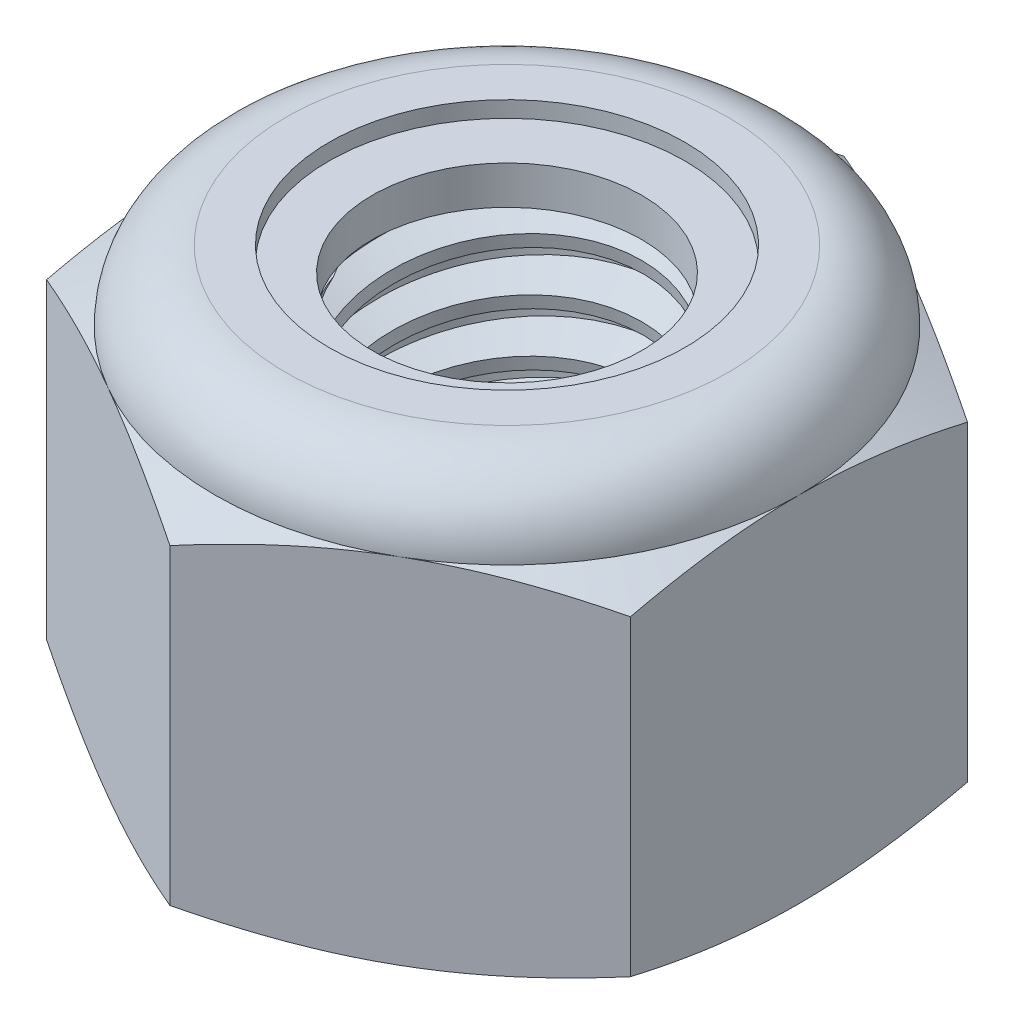
SolidWorks part; units mm, degrees
material "Stainless Steel (ferritic)"
ref_plane "Front" through (0, 0, 0) normal (0, 0, 1) x (1, 0, 0)
ref_plane "Top" through (0, 0, 0) normal (0, 1, 0) x (1, 0, 0)
ref_plane "Right" through (0, 0, 0) normal (1, 0, 0) x (0, 0, -1)
sketch "Sketch1" plane through (0, 0, 0) normal (0, 1, 0) x (1, 0, 0)
  line L1 (0, 3.1754) -> (-2.75, 1.5877)
  line L2 (-2.75, 1.5877) -> (-2.75, -1.5877)
  line L3 (-2.75, -1.5877) -> (0, -3.1754)
  line L4 (0, -3.1754) -> (2.75, -1.5877)
  line L5 (2.75, -1.5877) -> (2.75, 1.5877)
  line L6 (2.75, 1.5877) -> (0, 3.1754)
  circle A0 centre (0, 0) radius 2.75 construction
  dimension "Hex Flats" = 5.5
extrude "Extrude1" add sketch "Sketch1" along normal blind 4
sketch "Sketch2" plane through (0, 0, 0) normal (1, 0, 0) x (0, 0, -1)
  line L0 (-1.5, 0) -> (-1.5, 4) construction
  line L1 (0, 0) -> (1.5, 0)
  line L2 (0, 0) -> (0, 4)
  line L3 (0, 4) -> (1.5, 4)
  line L4 (1.5, 0) -> (1.5, 4)
  line L5 (-1.5877, 4) -> (1.5877, 4) construction
  line L7 (0, -1.5) -> (0, 0) construction
  dimension "Thread Dia" = 3
revolve "Revolve1" add sketch "Sketch2" angle 360 about L7
sketch "Sketch3" plane through (0, 0, 0) normal (1, 0, 0) x (0, 0, -1)
  line L0 (1.5, 4) -> (-1.5, 4) construction
  line L1 (-1.5, 4) -> (-1.5, 3.5) construction
  line L2 (-1.5, 3.5) -> (1.5, 4) construction
  line L3 (1.5, 4) -> (1.5103, 3.9384) construction
  line L4 (1.5103, 3.9384) -> (1.5822, 3.5068)
  line L5 (1.5822, 3.5068) -> (1.2896, 3.6164)
  line L6 (1.2896, 3.6164) -> (1.269, 3.7397)
  line L7 (1.269, 3.7397) -> (1.5103, 3.9384)
  line L8 (1.2793, 3.6781) -> (1.5462, 3.7226) construction
  line L9 (1.5, 4) -> (1.5, 3.7149) construction
  line L10 (1.5, 3.7149) -> (-1.5, 3.2149) construction
  line L11 (-1.5, 3.2149) -> (-1.5, 3.5) construction
  line L12 (-0.0892, 4) -> (0.0892, 2.9297) construction
  line L13 (-1.5, 0) -> (-1.5, 4) construction
  line L14 (0, 4) -> (1.5, 4) construction
  line L15 (1.5, 0) -> (1.5, 4) construction
  point P13 (0, 3.4649)
  dimension "D1" = 0.0625
  dimension "D2" = 0.125
  dimension "Thread Pitch" = 0.5
  dimension "D4" = 60
  dimension "D5" = 0.5
revolve "Cut-Revolve1" cut sketch "Sketch3" angle 360 about L12
pattern_linear "LPattern1" count 8 spacing 0.5 along (0, -1, 0) count 2 spacing 0.5 along (0, 1, 0) of "Cut-Revolve1"
sketch "Sketch4" plane through (0, 0, 0) normal (1, 0, 0) x (0, 0, -1)
  line L0 (0, 4) -> (1.5, 4)
  line L1 (1.5, 4) -> (1.269, 3.8923)
  line L2 (1.269, 3.8923) -> (1.269, 0.1077)
  line L3 (1.269, 0.1077) -> (1.5, 0)
  line L4 (1.5, 0) -> (0, 0)
  line L5 (0, 0) -> (0, 4)
  line L6 (1.5, 0) -> (1.5, 4) construction
  line L7 (0, 4) -> (1.5, 4) construction
  line L8 (0, 0) -> (1.5, 0) construction
  line L9 (0, 0) -> (0, 4) construction
  line L10 (0, 4) -> (0, 4.2549) construction
  dimension "D1" = 25
revolve "Cut-Revolve2" cut sketch "Sketch4" angle 360 about L10
combine bodies "Combine1" operation type subtract main body 112 bodies to subtract 111
sketch "Sketch5" plane through (0, 0, 0) normal (1, 0, 0) x (0, 0, -1)
  line L0 (0, 0) -> (2.75, 0)
  line L1 (2.75, 0) -> (3.1754, 0.1984)
  line L2 (3.1754, 0.1984) -> (3.1754, 3.135)
  line L3 (3.1754, 3.135) -> (2.75, 3.3333)
  line L4 (2.0833, 4) -> (2.0833, 5.27)
  line L5 (2.0833, 5.27) -> (4.4454, 5.27)
  line L6 (4.4454, 5.27) -> (4.4454, -1.27)
  line L7 (4.4454, -1.27) -> (0, -1.27)
  line L8 (0, -1.27) -> (0, 0)
  line L9 (2.75, 3.3333) -> (2.75, 0) construction
  line L10 (0, 0) -> (1.5, 0) construction
  line L13 (3.1754, 1.6667) -> (4.4454, 1.6667) construction
  line L14 (3.1754, 4) -> (3.1754, 0) construction
  line L15 (0, 0) -> (0, 5.27) construction
  line L20 (0, 5.27) -> (2.0833, 5.27) construction
  line L22 (0, 4) -> (1.5, 4) construction
  arc A0 (2.75, 3.3333) -> (2.0833, 4) centre (2.0833, 3.3333) ccw
  dimension "D1" = 25
  dimension "D2" = 1.27
  dimension "D3" = 4
  dimension "D4" = 0.6667
revolve "Cut-Revolve3" cut sketch "Sketch5" angle 360 about L15
sketch "Sketch6" plane through (0, 0, 0) normal (1, 0, 0) x (0, 0, -1)
  line L0 (0, 3.3333) -> (2.5976, 3.3333)
  line L1 (2.0833, 3.8476) -> (1.6762, 3.8476)
  line L2 (0, 5.27) -> (0, 3.3333)
  line L3 (1.6762, 5.27) -> (0, 5.27)
  line L4 (0, 5.27) -> (2.0833, 5.27) construction
  line L5 (0, 0) -> (0, 5.27) construction
  line L6 (0, 5.27) -> (0, 44.323) construction
  line L7 (1.6762, 3.8476) -> (1.6762, 5.27)
  line L8 (2.0833, 4) -> (2.0833, 3.8476) construction
  line L9 (1.6762, 3.8476) -> (1.269, 3.8476) construction
  line L10 (1.269, 3.8476) -> (1.269, 3.8923) construction
  arc A0 (2.5976, 3.3333) -> (2.0833, 3.8476) centre (2.0833, 3.3333) ccw
  arc A1 (2.75, 3.3333) -> (2.0833, 4) centre (2.0833, 3.3333) ccw construction
  dimension "D1" = 0.1524
revolve "Cut-Revolve4" cut sketch "Sketch6" angle 360 about L6
sketch "Sketch7" plane through (0, 0, 0) normal (1, 0, 0) x (0, 0, -1)
  line L0 (1.269, 3.4095) -> (2.5147, 3.4095)
  line L1 (2.0833, 3.7714) -> (1.269, 3.7714)
  line L2 (1.269, 3.7714) -> (1.269, 3.4095)
  line L3 (1.269, 3.4095) -> (0, 3.4095) construction
  line L4 (0, 3.4095) -> (0, 3.7714) construction
  line L5 (0, 3.7714) -> (1.269, 3.7714) construction
  line L6 (1.269, 3.4095) -> (1.269, 3.3333) construction
  line L7 (0, 3.3333) -> (2.5976, 3.3333) construction
  line L8 (2.0833, 3.7714) -> (2.0833, 3.8476) construction
  arc A0 (2.5147, 3.4095) -> (2.0833, 3.7714) centre (2.0833, 3.3333) ccw
  arc A2 (2.5976, 3.3333) -> (2.0833, 3.8476) centre (2.0833, 3.3333) ccw construction
  dimension "D1" = 0.0762
revolve "Revolve2" add sketch "Sketch7" angle 360 about L4
equation "\"D1@Sketch3\"=\"Thread Pitch@Sketch3\"/8"
equation "\"D2@Sketch3\"=\"Thread Pitch@Sketch3\"/4"
equation "\"D5@Sketch3\"=\"Thread Pitch@Sketch3\""
equation "\"D4@LPattern1\"=\"Thread Pitch@Sketch3\""
equation "\"D3@LPattern1\"=\"Thread Pitch@Sketch3\""
equation "\"D1@LPattern1\"=\"Height@Extrude1\"/\"Thread Pitch@Sketch3\""
equation "\"D4@Sketch5\"=\"Height@Extrude1\"/6"
